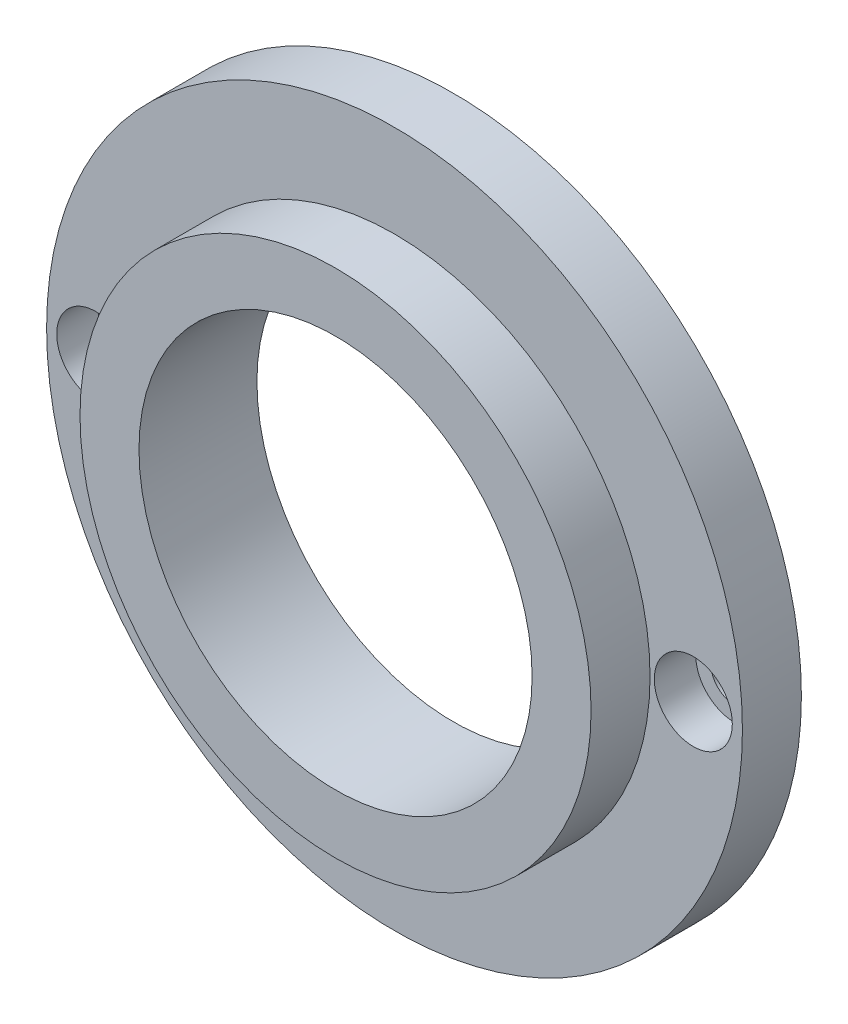
SolidWorks part; units mm, degrees
ref_plane "Plan de face" through (0, 0, 0) normal (0, 0, 1) x (1, 0, 0)
ref_plane "Plan de dessus" through (0, 0, 0) normal (0, 1, 0) x (1, 0, 0)
ref_plane "Plan de droite" through (0, 0, 0) normal (1, 0, 0) x (0, 0, -1)
sketch "Esquisse1" [suppressed] plane through (0, 0, 0) normal (0, 0, 1) x (1, 0, 0)
  circle A0 centre (0, 0) radius 40.8746
sketch "Esquisse10" plane through (0, 0, 0) normal (0, 0, 1) x (1, 0, 0)
  circle A0 centre (0, 0) radius 13
  circle A1 centre (0, 0) radius 10
extrude "Boss.-Extru.2" add sketch "Esquisse10" along normal blind 3
sketch "Esquisse11" plane through (0, 0, 0) normal (0, 0, -1) x (-1, 0, 0)
  circle A0 centre (0, 0) radius 10
  circle A1 centre (0, 0) radius 17.7
extrude "Boss.-Extru.3" add sketch "Esquisse11" along normal blind 3
sketch "Sketch1" plane through (0, 0, 0) normal (0, 0, 1) x (1, 0, 0)
  line L0 (-15.2, 0) -> (-17.7, 0)
  line L1 (15.2, 0) -> (17.7, 0)
  circle A2 centre (0, 0) radius 17.7 construction
hole_wizard "CBORE for #2 Fillister Head Machine Screw1" positions "Sketch2" profile "Sketch3" counterbore size "#2" standard "ANSI Inch" end condition through all
sketch "Sketch2" plane through (0, 0, 0) normal (0, 0, 1) x (1, 0, 0)
  point P0 (-15.2, 0)
  point P3 (15.2, 0)
sketch "Sketch3" plane through (-15.2, 0, 0) normal (1, 0, 0) x (0, -1, 0)
  line L0 (0, 0) -> (0, 3)
  line L1 (0, 3) -> (1.2192, 3)
  line L3 (1.2192, 3) -> (1.2192, 2.1082)
  line L4 (1.2192, 2.1082) -> (1.985, 2.1082)
  line L5 (1.985, 2.1082) -> (1.985, 0)
  line L7 (1.985, 0) -> (0, 0)
  line L11 (0, -6.35) -> (0, 107.95) construction
  dimension "Thru Hole Dia." = 2.4384
  dimension "Thru Hole Depth" = 3
  dimension "C'Bore Dia." = 3.97
  dimension "C'Bore Depth" = 2.1082
